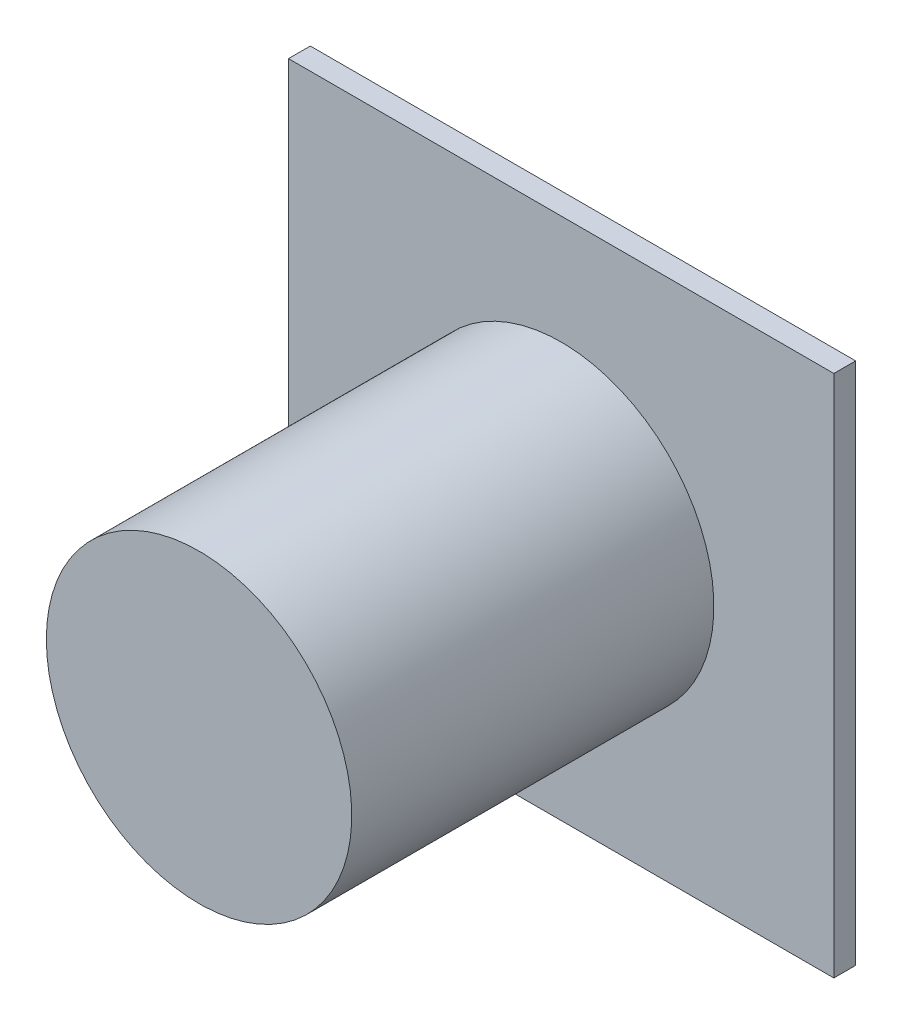
SolidWorks part; units mm, degrees
ref_plane "前视基准面" through (0, 0, 0) normal (0, 0, 1) x (1, 0, 0)
ref_plane "上视基准面" through (0, 0, 0) normal (0, 1, 0) x (1, 0, 0)
ref_plane "右视基准面" through (0, 0, 0) normal (1, 0, 0) x (0, 0, -1)
other "Configuration Table"
sketch "草图1" plane through (0, 0, 0) normal (0, 0, 1) x (1, 0, 0)
  line L1 (-12.5, -12) -> (12.5, -12)
  line L2 (-12.5, -12) -> (-12.5, 12)
  line L3 (-12.5, 12) -> (12.5, 12)
  line L4 (12.5, -12) -> (12.5, 12)
extrude "25x24PCB示意" add sketch "草图1" along normal blind 1
sketch "草图2" plane through (0, 0, 0) normal (0, 0, 1) x (1, 0, 0)
  circle A0 centre (0, 0) radius 7
extrude "14mm镜头前端外形示意" add sketch "草图2" along normal blind 16.6 from offset 1
